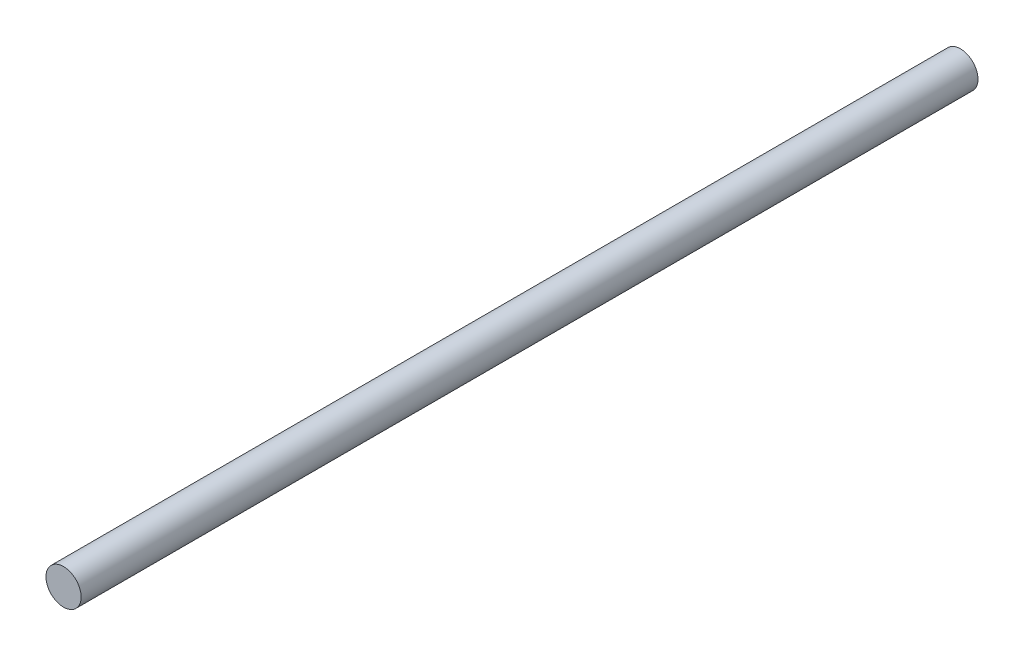
SolidWorks part; units mm, degrees
ref_plane "Plan de face" through (0, 0, 0) normal (0, 0, 1) x (1, 0, 0)
ref_plane "Plan de dessus" through (0, 0, 0) normal (0, 1, 0) x (1, 0, 0)
ref_plane "Plan de droite" through (0, 0, 0) normal (1, 0, 0) x (0, 0, -1)
sketch "Esquisse1" plane through (0, 0, 0) normal (0, 0, 1) x (1, 0, 0)
  circle A0 centre (0, 0) radius 5
  dimension "D1" = 10
extrude "Boss.-Extru.1" add sketch "Esquisse1" along normal blind 255
